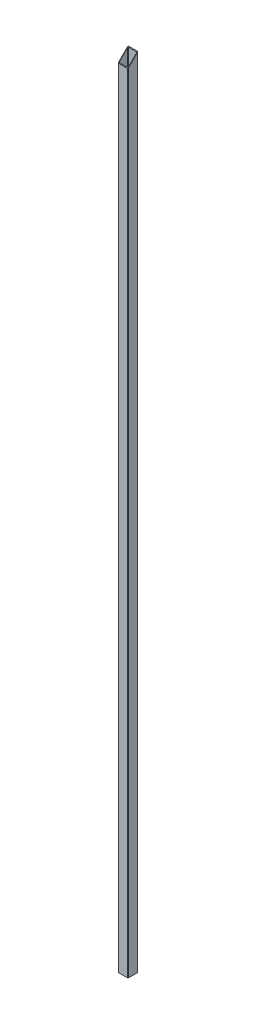
SolidWorks part; units mm, degrees
ref_plane "Спереди" through (0, 0, 0) normal (0, 0, 1) x (1, 0, 0)
ref_plane "Сверху" through (0, 0, 0) normal (0, 1, 0) x (1, 0, 0)
ref_plane "Справа" through (0, 0, 0) normal (1, 0, 0) x (0, 0, -1)
sketch "Эскиз2" plane through (0, 0, 0) normal (0, 1, 0) x (1, 0, 0)
  line L1 (-18, 20) -> (18, 20)
  line L2 (-20, 18) -> (-20, -18)
  line L3 (-18, -20) -> (18, -20)
  line L4 (20, 18) -> (20, -18)
  line L5 (-20, 20) -> (20, -20) construction
  line L6 (-20, -20) -> (20, 20) construction
  line L7 (16, -18) -> (-16, -18)
  line L8 (18, -16) -> (18, 16)
  line L9 (16, 18) -> (-16, 18)
  line L10 (-18, -16) -> (-18, 16)
  line L11 (18, -18) -> (-18, 18) construction
  line L12 (18, 18) -> (-18, -18) construction
  arc A0 (16, -18) -> (18, -16) centre (16, -16) ccw
  arc A1 (18, -20) -> (20, -18) centre (18, -18) ccw
  arc A2 (-20, -18) -> (-18, -20) centre (-18, -18) ccw
  arc A3 (-16, -18) -> (-18, -16) centre (-16, -16) cw
  arc A4 (18, 20) -> (20, 18) centre (18, 18) cw
  arc A5 (18, 16) -> (16, 18) centre (16, 16) ccw
  arc A6 (-18, 20) -> (-20, 18) centre (-18, 18) ccw
  arc A7 (-16, 18) -> (-18, 16) centre (-16, 16) ccw
  point P0 (0, 0)
  point P6 (0, 0)
  dimension "D5" = 2
  dimension "D1" = 40
  dimension "D2" = 40
  dimension "D3" = 2
  dimension "D4" = 2
extrude "Бобышка-Вытянуть1" add sketch "Эскиз2" along normal blind 3200
sketch "Эскиз3" plane through (20, 0, 0) normal (1, 0, 0) x (0, 0, -1)
  line L0 (20, 3200) -> (-20, 3200)
  line L1 (-20, 3200) -> (-20, 3160)
  line L2 (-20, 3200) -> (-20, 0) construction
  line L3 (-20, 3160) -> (20, 3200)
  dimension "D1" = 45
extrude "Вырез-Вытянуть1" cut sketch "Эскиз3" against normal through all
